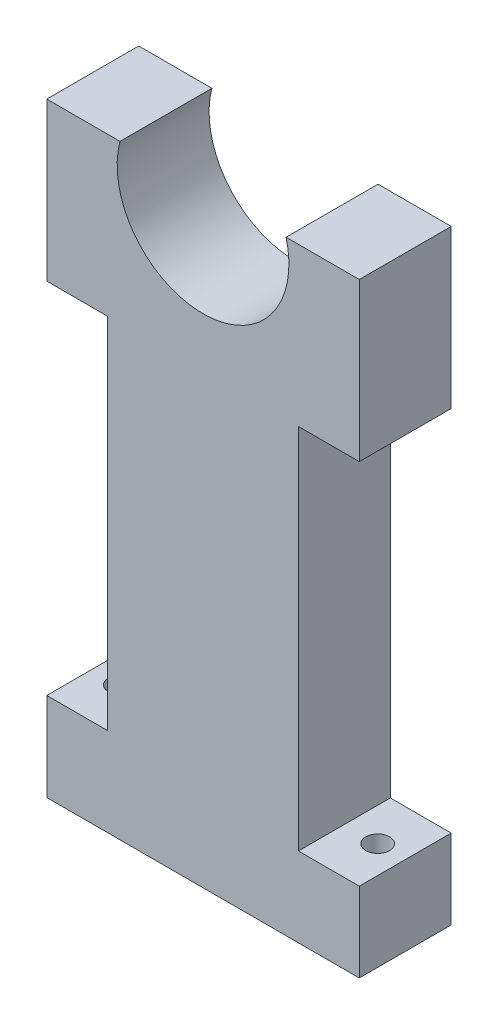
SolidWorks part; units mm, degrees
ref_plane "Front Plane" through (0, 0, 0) normal (0, 0, 1) x (1, 0, 0)
ref_plane "Top Plane" through (0, 0, 0) normal (0, 1, 0) x (1, 0, 0)
ref_plane "Right Plane" through (0, 0, 0) normal (1, 0, 0) x (0, 0, -1)
sketch "Sketch1" plane through (0, 0, 0) normal (0, 0, 1) x (1, 0, 0)
  line L0 (0, 0) -> (43.18, 0)
  line L1 (43.18, 0) -> (43.18, 10.9904)
  line L2 (43.18, 10.9904) -> (34.7679, 10.9904)
  line L3 (34.7679, 10.9904) -> (34.7679, 61.7904)
  line L4 (34.7679, 61.7904) -> (43.18, 61.7904)
  line L5 (43.18, 61.7904) -> (43.18, 83.5801)
  line L6 (43.18, 83.5801) -> (33.0639, 83.5801)
  line L7 (0, 83.5801) -> (0, 61.7904)
  line L8 (0, 61.7904) -> (8.4121, 61.7904)
  line L9 (8.4121, 61.7904) -> (8.4121, 12.2171)
  line L10 (8.4121, 12.2171) -> (0, 12.2171)
  line L11 (0, 12.2171) -> (0, 0)
  line L12 (21.59, 94.36) -> (21.59, -21.1705) construction
  line L13 (10.1161, 83.5801) -> (0, 83.5801)
  arc A0 (10.1161, 83.5801) -> (33.0639, 83.5801) centre (21.59, 80.5558) ccw
  dimension "D3" = 11.8658
  dimension "D1" = 43.18
  dimension "D2" = 50.8
extrude "Boss-Extrude1" add sketch "Sketch1" along normal blind 12.7
sketch "Sketch2" plane through (0, 0, 0) normal (0, -1, 0) x (1, 0, 0)
  line L0 (0, 6.35) -> (43.18, 6.35) construction
  line L1 (0, 12.7) -> (0, 0) construction
  line L2 (43.18, 12.7) -> (43.18, 0) construction
  circle A0 centre (3.81, 6.35) radius 1.651
  circle A1 centre (39.37, 6.35) radius 1.651
  dimension "D1" = 3.302
  dimension "D2" = 3.81
  dimension "D3" = 3.81
extrude "Cut-Extrude1" cut sketch "Sketch2" against normal up to next
